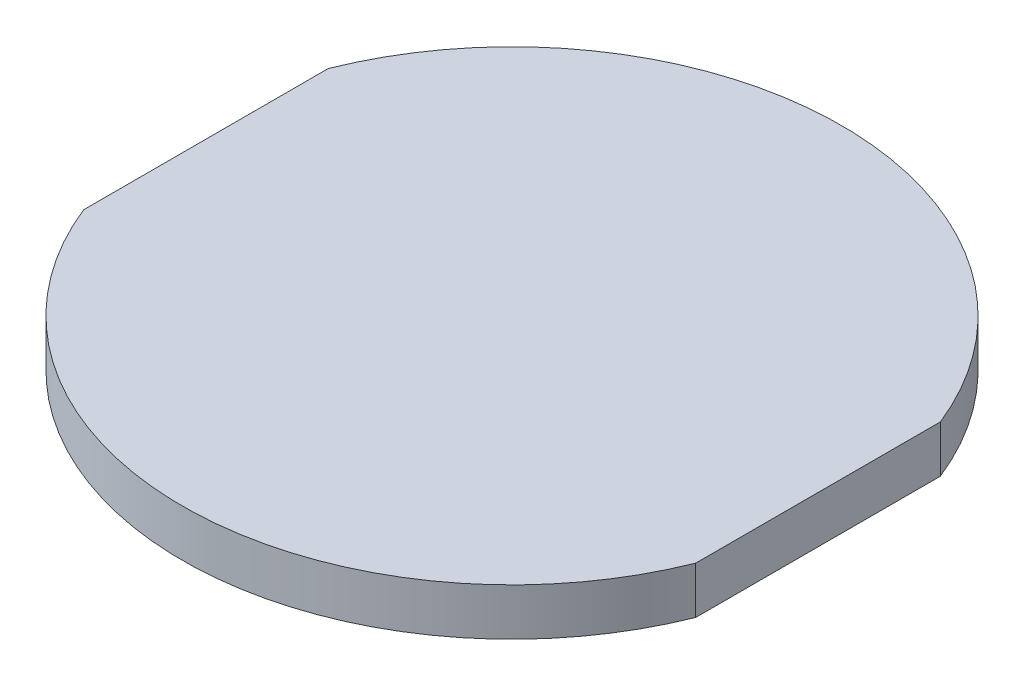
SolidWorks part; units mm, degrees
ref_plane "Front Plane" through (0, 0, 0) normal (0, 0, 1) x (1, 0, 0)
ref_plane "Top Plane" through (0, 0, 0) normal (0, 1, 0) x (1, 0, 0)
ref_plane "Right Plane" through (0, 0, 0) normal (1, 0, 0) x (0, 0, -1)
sketch "Sketch2" plane through (0, 0, 0) normal (0, 1, 0) x (1, 0, 0)
  line L2 (-6.5, 2.5981) -> (-6.5, -2.5981)
  line L4 (6.5, 2.5981) -> (6.5, -2.5981)
  line L5 (-4.0532, 5.7072) -> (4.0532, -5.7072) construction
  line L6 (-4.0532, -5.7072) -> (4.0532, 5.7072) construction
  arc A0 (6.5, 2.5981) -> (-6.5, 2.5981) centre (0, 0) ccw
  arc A1 (-6.5, -2.5981) -> (6.5, -2.5981) centre (0, 0) ccw
  dimension "D1" = 7
  dimension "D2" = 13
  dimension "D3" = 6.5
extrude "Boss-Extrude1" add sketch "Sketch2" along normal blind 1
